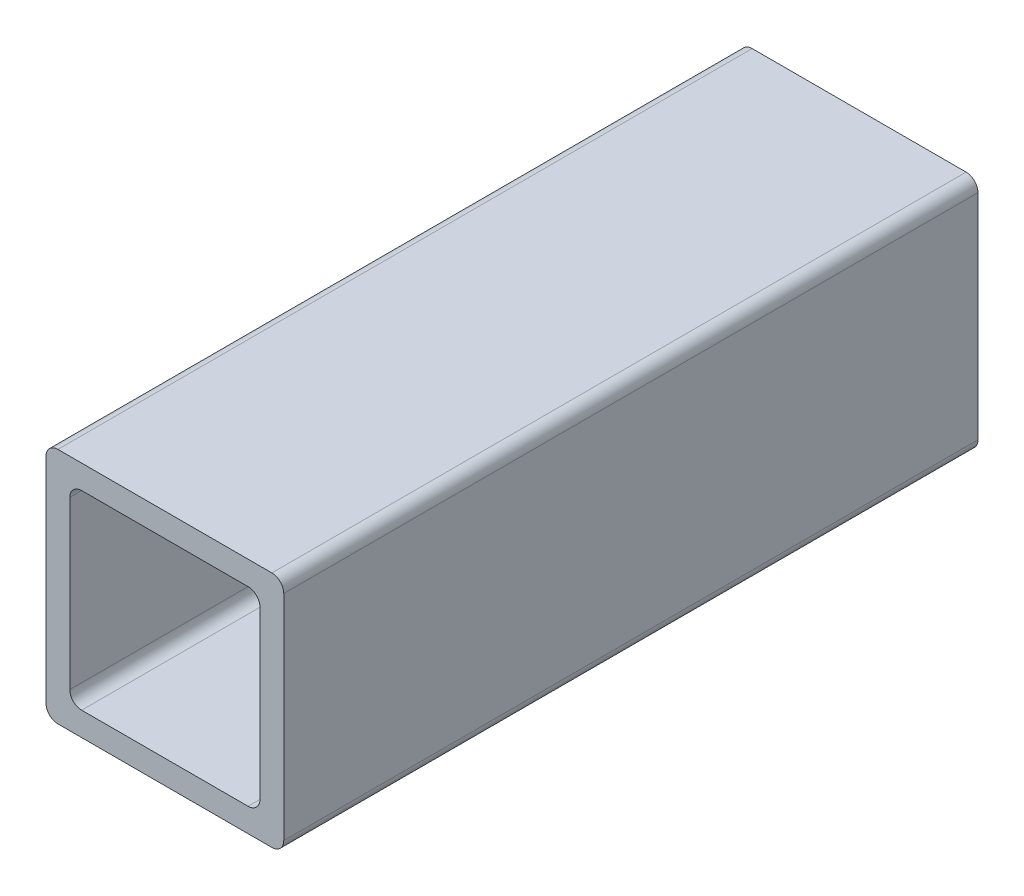
SolidWorks part; units mm, degrees
ref_plane "Front Plane" through (0, 0, 0) normal (0, 0, 1) x (1, 0, 0)
ref_plane "Top Plane" through (0, 0, 0) normal (0, 1, 0) x (1, 0, 0)
ref_plane "Right Plane" through (0, 0, 0) normal (1, 0, 0) x (0, 0, -1)
sketch "Sketch1" plane through (0, 0, -3.048) normal (0, 0, 1) x (1, 0, 0)
  line L1 (12.7, -12.7) -> (-12.7, -12.7)
  line L2 (12.7, -12.7) -> (12.7, 12.7)
  line L3 (12.7, 12.7) -> (-12.7, 12.7)
  line L4 (-12.7, -12.7) -> (-12.7, 12.7)
  line L5 (12.7, -12.7) -> (-12.7, 12.7) construction
  line L6 (12.7, 12.7) -> (-12.7, -12.7) construction
  line L7 (10.16, -10.16) -> (-10.16, -10.16)
  line L8 (10.16, -10.16) -> (10.16, 10.16)
  line L9 (10.16, 10.16) -> (-10.16, 10.16)
  line L10 (-10.16, -10.16) -> (-10.16, 10.16)
  line L11 (10.16, -10.16) -> (-10.16, 10.16) construction
  line L12 (10.16, 10.16) -> (-10.16, -10.16) construction
  point P0 (0, 0)
  point P6 (0, 0)
  dimension "D1" = 25.4
  dimension "D2" = 2.54
extrude "Boss-Extrude2" add sketch "Sketch1" along normal up to surface (74.168 mm away)
fillet "Fillet1" radius 1.27 8 edges at (-10.16, -10.16, 34.036) (10.16, 10.16, 34.036) (-10.16, 10.16, 34.036) (10.16, -10.16, 34.036) (12.7, -12.7, 34.036) (-12.7, -12.7, 34.036) (12.7, 12.7, 34.036) (-12.7, 12.7, 34.036)
